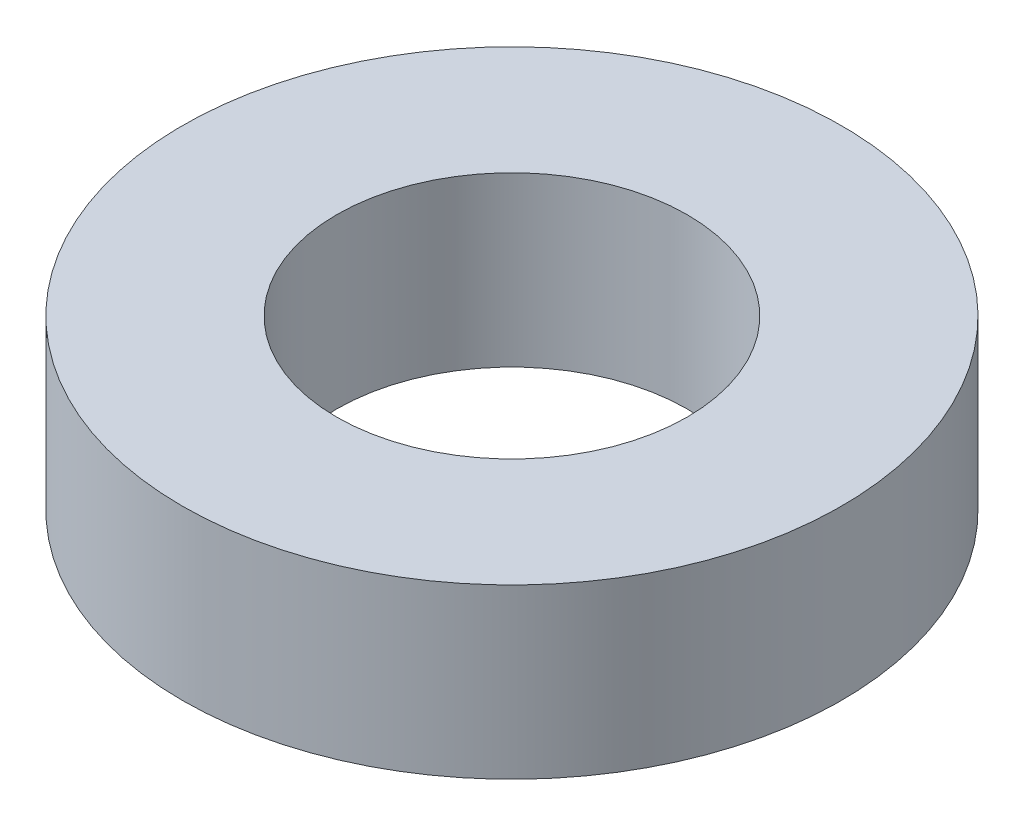
SolidWorks part; units mm, degrees
ref_plane "前视基准面" through (0, 0, 0) normal (0, 0, 1) x (1, 0, 0)
ref_plane "上视基准面" through (0, 0, 0) normal (0, 1, 0) x (1, 0, 0)
ref_plane "右视基准面" through (0, 0, 0) normal (1, 0, 0) x (0, 0, -1)
other "Configuration Table"
sketch "草图1" plane through (0, 0, 0) normal (0, 1, 0) x (1, 0, 0)
  circle A0 centre (0, 0) radius 12.5
  circle A1 centre (0, 0) radius 23.5
  dimension "D1" = 25
  dimension "D2" = 47
extrude "凸台-拉伸2" add sketch "草图1" along normal blind 12
